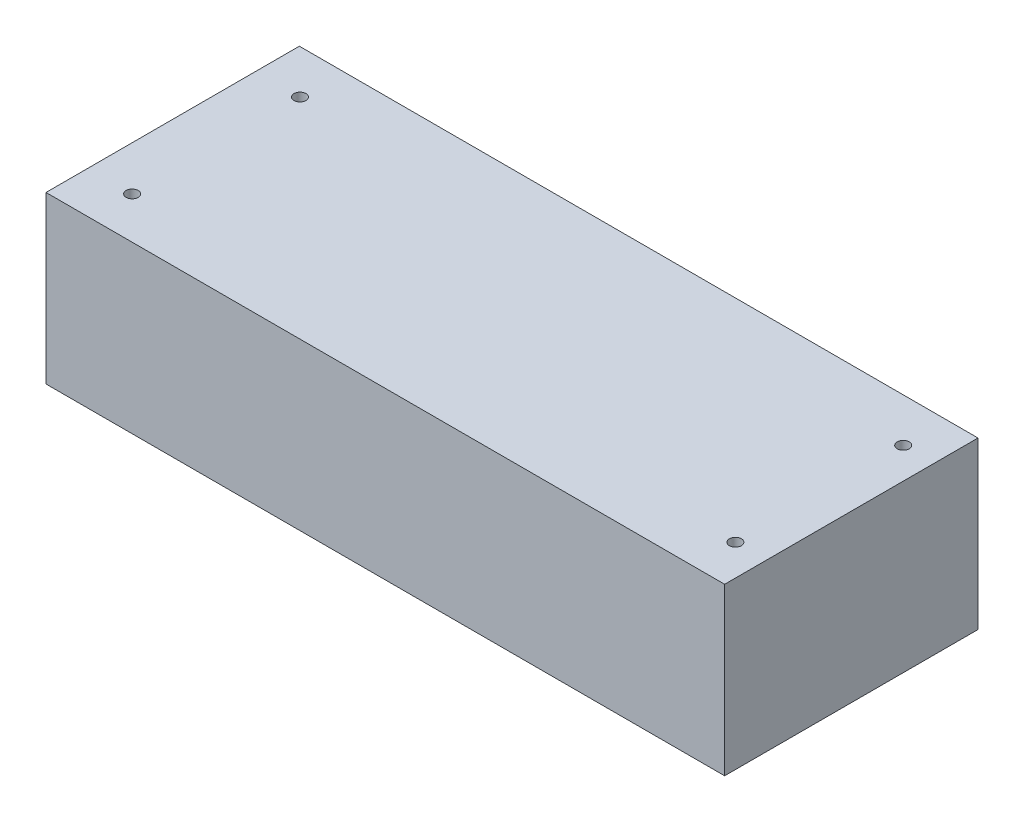
SolidWorks part; units mm, degrees
material "Acrylic (Medium-high impact)"
ref_plane "Front Plane" through (0, 0, 0) normal (0, 0, 1) x (1, 0, 0)
ref_plane "Top Plane" through (0, 0, 0) normal (0, 1, 0) x (1, 0, 0)
ref_plane "Right Plane" through (0, 0, 0) normal (1, 0, 0) x (0, 0, -1)
sketch "Sketch1" plane through (0, 0, 0) normal (0, 0, 1) x (1, 0, 0)
  line L0 (0, 0) -> (225, 0)
  line L1 (0, 0) -> (0, -55)
  line L2 (225, 0) -> (225, -55)
  line L3 (0, -55) -> (225, -55)
  dimension "D1" = 225
  dimension "D2" = 55
extrude "Boss-Extrude1" add sketch "Sketch1" along normal blind 84
shell "Shell1" thickness 4
sketch "Sketch2" plane through (0, -4, 0) normal (0, -1, 0) x (1, 0, 0)
  circle A1 centre (14.7075, 70.1438) radius 2
  circle A2 centre (14.7075, 70.1438) radius 2
  circle A3 centre (14.7075, 14.5) radius 2
  circle A4 centre (14.7075, 14.5) radius 2
  circle A5 centre (214.7075, 70.1438) radius 2
  circle A6 centre (214.7075, 70.1438) radius 2
  circle A7 centre (214.7075, 14.5) radius 2
  circle A8 centre (214.7075, 14.5) radius 2
  dimension "D1" = 0
  dimension "D2" = 0
  dimension "D3" = 0
  dimension "D4" = 0
extrude "Cut-Extrude1" cut sketch "Sketch2" against normal through all
